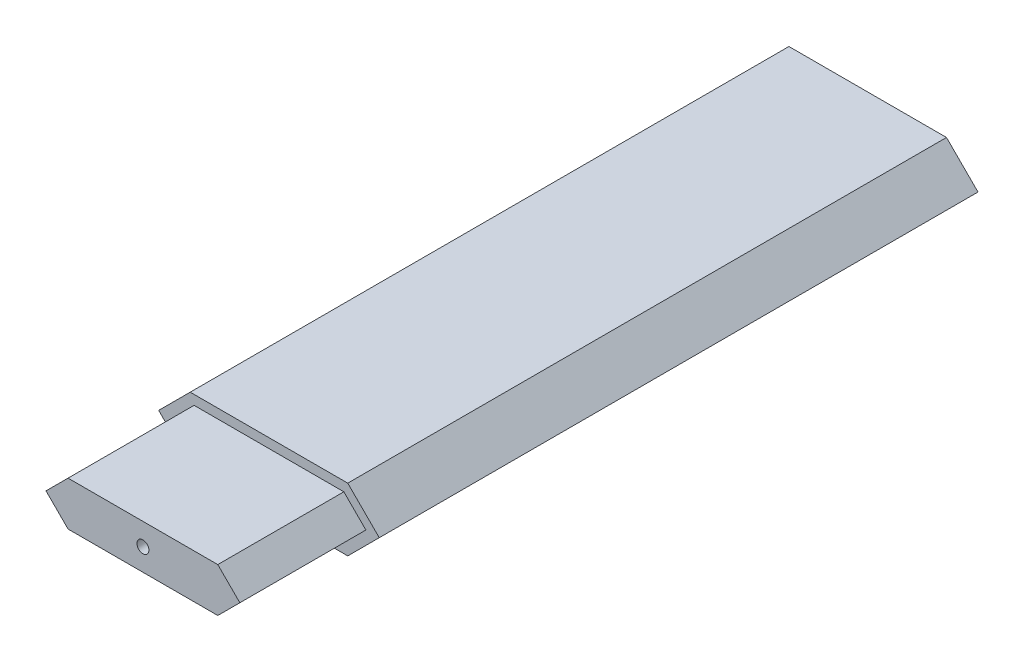
SolidWorks part; units mm, degrees
ref_plane "前视基准面" through (0, 0, 0) normal (0, 0, 1) x (1, 0, 0)
ref_plane "上视基准面" through (0, 0, 0) normal (0, 1, 0) x (1, 0, 0)
ref_plane "右视基准面" through (0, 0, 0) normal (1, 0, 0) x (0, 0, -1)
sketch "草图1" plane through (0, 0, 0) normal (0, 1, 0) x (1, 0, 0)
  line L0 (0, 0) -> (0, 690) construction
  line L1 (0, 690) -> (0, 630) construction
  line L2 (-35, 0) -> (35, 0)
  line L3 (-35, 0) -> (-35, 630)
  line L4 (-35, 630) -> (0, 690)
  line L5 (35, 630) -> (0, 690)
  line L6 (35, 0) -> (35, 630)
  dimension "D1" = 690
  dimension "D2" = 60
  dimension "D3" = 70
ref_plane "基准面1" through (0, 10, 0) normal (0, 1, 0) x (1, 0, 0)
sketch "草图4" plane through (0, 10, 0) normal (0, 1, 0) x (1, 0, 0)
  line L0 (25, 0) -> (-25, 0)
  line L1 (-25, 0) -> (-25, 630)
  line L2 (-25, 630) -> (0, 672.8571)
  line L3 (0, 0) -> (0, 690) construction
  line L4 (-35, 630) -> (0, 690) construction
  line L5 (0, -5.5) -> (0, 5.5) construction
  line L6 (25, 630) -> (0, 672.8571)
  line L7 (25, 0) -> (25, 630)
  point P2 (0, 0)
  dimension "D1" = 50
loft "放样1" add profiles "草图4", "草图1"
mirror "镜向1" about plane through (0, 0, 0) normal (0, 1, 0) of "放样1"
sketch "草图5" plane through (0, 0, 0) normal (0, 1, 0) x (1, 0, 0)
  line L0 (0, -30.5) -> (0, -55.5) construction
  line L1 (0, -55.5) -> (0, -30.5) construction
  line L2 (-79, -30.5) -> (79, -30.5) construction
  line L3 (0, -30.5) -> (0, 0) construction
  arc A0 (-66.3468, -65.1892) -> (66.3468, -65.1892) centre (0, -287.5) cw
  arc A1 (76.7912, -2.3877) -> (76.7912, -58.6123) centre (-101, -30.5) cw
  arc A2 (-76.7912, -2.3877) -> (-76.7912, -58.6123) centre (101, -30.5) ccw
  arc A4 (66.3468, -65.1892) -> (76.7912, -58.6123) centre (68.6918, -57.3316) ccw
  arc A5 (-66.3468, -65.1892) -> (-76.7912, -58.6123) centre (-68.6918, -57.3316) cw
  arc A6 (-76.7912, -2.3877) -> (76.7912, -2.3877) centre (0, 224.9955) ccw
  point P10 (0, -55.5)
  point P15 (79, -30.5)
  dimension "D4" = 232
  dimension "D5" = 180
  dimension "D6" = 8.2
  dimension "D7" = 240
  dimension "D1" = 25
  dimension "D2" = 158
  dimension "D3" = 30.5
extrude "凸台-拉伸1" add sketch "草图5" along normal mid plane 36 separate body
chamfer "倒角1" distance 5 angle 45 11 edges at (79, -18, 30.5) (73.0612, -18, 64.2705) (0, -18, 55.5) (-73.0612, -18, 64.2705) (-79, -18, 30.5) (79, 18, 30.5) (73.0612, 18, 64.2705) (0, 18, 55.5) (-73.0612, 18, 64.2705) (-79, 18, 30.5) (0, 18, 15.0045)
chamfer "倒角2" distance 5 angle 45 1 edges at (0, -18, 15.0045)
sketch "草图6" plane through (0, 18, 0) normal (0, 1, 0) x (1, 0, 0)
  arc A12 (67.2218, -55.0237) -> (68.3355, -15.4837) centre (-101, -30.5) ccw
  arc A13 (-68.3355, -15.4837) -> (68.3355, -15.4837) centre (0, 224.9955) ccw
  arc A14 (-68.3355, -15.4837) -> (-67.2218, -55.0237) centre (101, -30.5) ccw
  arc A15 (67.2218, -55.0237) -> (-67.2218, -55.0237) centre (0, -287.5) ccw
  arc A16 (67.2218, -55.0237) -> (68.3355, -15.4837) centre (-101, -30.5) ccw
  arc A17 (-68.3355, -15.4837) -> (68.3355, -15.4837) centre (0, 224.9955) ccw
  arc A18 (-68.3355, -15.4837) -> (-67.2218, -55.0237) centre (101, -30.5) ccw
  arc A19 (67.2218, -55.0237) -> (-67.2218, -55.0237) centre (0, -287.5) ccw
  dimension "D1" = 5
extrude "切除-拉伸1" cut sketch "草图6" against normal blind 8
mirror "镜向2" about plane through (0, 0, 0) normal (0, 1, 0) of "切除-拉伸1"
sketch "草图7" plane through (0, 0, 0) normal (0, 0, 1) x (1, 0, 0)
  line L12 (-25.8284, 12) -> (-37.8284, 0)
  line L13 (-37.8284, 0) -> (-25.8284, -12)
  line L14 (-25.8284, -12) -> (25.8284, -12)
  line L15 (25.8284, -12) -> (37.8284, 0)
  line L16 (37.8284, 0) -> (25.8284, 12)
  line L17 (25.8284, 12) -> (-25.8284, 12)
  line L18 (-25.8284, 12) -> (-37.8284, 0)
  line L19 (-37.8284, 0) -> (-25.8284, -12)
  line L20 (-25.8284, -12) -> (25.8284, -12)
  line L21 (25.8284, -12) -> (37.8284, 0)
  line L22 (37.8284, 0) -> (25.8284, 12)
  line L23 (25.8284, 12) -> (-25.8284, 12)
  dimension "D1" = 2
extrude "凸台-拉伸2" add sketch "草图7" along normal up to surface (12.0045 mm away)
sketch "草图8" plane through (0, 0, 0) normal (0, 0, -1) x (-1, 0, 0)
  line L6 (25.8284, 12) -> (-25.8284, 12)
  line L7 (-25.8284, 12) -> (-37.8284, 0)
  line L8 (-37.8284, 0) -> (-25.8284, -12)
  line L9 (-25.8284, -12) -> (25.8284, -12)
  line L10 (25.8284, -12) -> (37.8284, 0)
  line L11 (37.8284, 0) -> (25.8284, 12)
  line L12 (25.8284, 12) -> (-25.8284, 12)
  line L13 (-25.8284, 12) -> (-37.8284, 0)
  line L14 (-37.8284, 0) -> (-25.8284, -12)
  line L15 (-25.8284, -12) -> (25.8284, -12)
  line L16 (25.8284, -12) -> (37.8284, 0)
  line L17 (37.8284, 0) -> (25.8284, 12)
  dimension "D1" = 0
extrude "凸台-拉伸3" add sketch "草图8" along normal blind 5
sketch "草图9" plane through (0, 0, 0) normal (0, 1, 0) x (1, 0, 0)
  line L0 (0, 690) -> (0, -310) construction
  line L1 (0, -310) -> (0, -234)
  line L2 (0, -310) -> (0, -256) construction
  line L3 (-22.5, -256) -> (22.5, -256) construction
  line L4 (-22.5, -256) -> (0, -310)
  line L6 (-22.5, -256) -> (-12, -234)
  line L7 (-12, -234) -> (0, -234)
  dimension "D1" = 1000
  dimension "D2" = 76
  dimension "D3" = 54
  dimension "D4" = 45
  dimension "D5" = 12
revolve "旋转1" add sketch "草图9" angle 360 about L0
sketch "草图10" plane through (0, 0, 234) normal (0, 0, -1) x (-1, 0, 0)
  circle A1 centre (0, 0) radius 12
  circle A2 centre (0, 0) radius 12
  dimension "D1" = 0
extrude "凸台-拉伸4" add sketch "草图10" along normal up to next
sketch "草图16" plane through (0, 0, 0) normal (0, 1, 0) x (1, 0, 0)
  line L0 (0, 690) -> (0, -15.0045) construction
  line L1 (35, 630) -> (0, 690) construction
  line L2 (0, 0) -> (0, -20) construction
  line L3 (0, 5) -> (0, -35)
  line L4 (-50, -35) -> (50, -35)
  line L5 (-50, -35) -> (-50, 195)
  line L6 (-50, 195) -> (50, 195)
  line L7 (50, -35) -> (50, 195)
  line L8 (25.8284, 5) -> (-25.8284, 5) construction
  line L9 (0, -35) -> (0, 195)
  line L10 (0, 195) -> (0, 155)
  line L11 (0, 155) -> (0, 385)
  line L12 (0, 385) -> (0, 345)
  line L13 (0, 345) -> (0, 575)
  line L14 (0, 575) -> (0, 535)
  line L15 (0, 535) -> (0, 690)
  arc A0 (-25.8284, -13.6106) -> (25.8284, -13.6106) centre (0, 224.9955) ccw construction
  dimension "D7" = 40
  dimension "D1" = 40
  dimension "D2" = 20
  dimension "D3" = 100
  dimension "D4" = 230
  dimension "D5" = 40
  dimension "D6" = 230
  dimension "D8" = 230
  dimension "D9" = 40
extrude "切除-拉伸7" cut sketch "草图16" against normal through all both and the other way through all flip side to cut
sketch "草图19" plane through (0, 0, 0) normal (0, 1, 0) x (1, 0, 0)
  line L0 (-50, -9.7384) -> (-50, -35)
  line L1 (-50, -35) -> (50, -35)
  line L2 (50, -35) -> (50, -9.7384)
  arc A0 (-50, -9.7384) -> (50, -9.7384) centre (0, 224.9955) ccw construction
  arc A1 (-50, -9.7384) -> (50, -9.7384) centre (0, 224.9955) ccw
extrude "切除-拉伸9" cut sketch "草图19" against normal through all both and the other way through all
sketch "草图20" plane through (0, 0, 0) normal (0, 0, 1) x (1, 0, 0)
  line L6 (-25.8284, 12) -> (-37.8284, 0)
  line L7 (-37.8284, 0) -> (-25.8284, -12)
  line L8 (-25.8284, -12) -> (25.8284, -12)
  line L9 (25.8284, -12) -> (37.8284, 0)
  line L10 (37.8284, 0) -> (25.8284, 12)
  line L11 (25.8284, 12) -> (-25.8284, 12)
  line L12 (-25.8284, 12) -> (-37.8284, 0)
  line L13 (-37.8284, 0) -> (-25.8284, -12)
  line L14 (-25.8284, -12) -> (25.8284, -12)
  line L15 (25.8284, -12) -> (37.8284, 0)
  line L16 (37.8284, 0) -> (25.8284, 12)
  line L17 (25.8284, 12) -> (-25.8284, 12)
  dimension "D1" = 0
extrude "凸台-拉伸5" add sketch "草图20" along normal blind 20
sketch "草图21" plane through (0, 0, 20) normal (0, 0, 1) x (1, 0, 0)
  circle A0 centre (0, 0) radius 1.9
  dimension "D1" = 3.8
extrude "切除-拉伸10" cut sketch "草图21" against normal through all both and the other way through all
sketch "草图29" plane through (0, 0, 20) normal (0, 0, 1) x (1, 0, 0)
  line L6 (25.8284, 12) -> (-25.8284, 12)
  line L7 (25.8284, 12) -> (-25.8284, 12)
  line L8 (-25.8284, 12) -> (-37.8284, 0)
  line L9 (-25.8284, 12) -> (-37.8284, 0)
  line L10 (-37.8284, 0) -> (-25.8284, -12)
  line L11 (-37.8284, 0) -> (-25.8284, -12)
  line L18 (-25.8284, -12) -> (25.8284, -12)
  line L19 (-25.8284, -12) -> (25.8284, -12)
  line L20 (25.8284, -12) -> (37.8284, 0)
  line L21 (25.8284, -12) -> (37.8284, 0)
  line L22 (37.8284, 0) -> (25.8284, 12)
  line L23 (37.8284, 0) -> (25.8284, 12)
  circle A0 centre (0, 0) radius 1.9 construction
  circle A1 centre (0, 0) radius 1.9
  dimension "D1" = 0
extrude "凸台-拉伸6" add sketch "草图29" along normal blind 15
sketch "草图33" plane through (0, 0, 35) normal (0, 0, 1) x (1, 0, 0)
  line L12 (30.7574, 0) -> (23.7574, 7)
  line L13 (23.7574, 7) -> (-23.7574, 7)
  line L14 (-23.7574, 7) -> (-30.7574, 0)
  line L15 (-30.7574, 0) -> (-23.7574, -7)
  line L16 (-23.7574, -7) -> (23.7574, -7)
  line L17 (23.7574, -7) -> (30.7574, 0)
  line L18 (30.7574, 0) -> (23.7574, 7)
  line L19 (23.7574, 7) -> (-23.7574, 7)
  line L20 (-23.7574, 7) -> (-30.7574, 0)
  line L21 (-30.7574, 0) -> (-23.7574, -7)
  line L22 (-23.7574, -7) -> (23.7574, -7)
  line L23 (23.7574, -7) -> (30.7574, 0)
  dimension "D1" = 5
extrude "切除-拉伸16" cut sketch "草图33" against normal blind 40 flip side to cut
sketch "草图31" plane through (0, 0, -195) normal (0, 0, -1) x (-1, 0, 0)
  line L12 (-28.2118, 0) -> (-23.0118, -5.2)
  line L13 (-23.0118, -5.2) -> (23.0118, -5.2)
  line L14 (23.0118, -5.2) -> (28.2118, 0)
  line L15 (28.2118, 0) -> (23.0118, 5.2)
  line L16 (23.0118, 5.2) -> (-23.0118, 5.2)
  line L17 (-23.0118, 5.2) -> (-28.2118, 0)
  line L18 (-28.2118, 0) -> (-23.0118, -5.2)
  line L19 (-23.0118, -5.2) -> (23.0118, -5.2)
  line L20 (23.0118, -5.2) -> (28.2118, 0)
  line L21 (28.2118, 0) -> (23.0118, 5.2)
  line L22 (23.0118, 5.2) -> (-23.0118, 5.2)
  line L23 (-23.0118, 5.2) -> (-28.2118, 0)
  dimension "D1" = 4.8
extrude "切除-拉伸15" cut sketch "草图31" against normal blind 41
